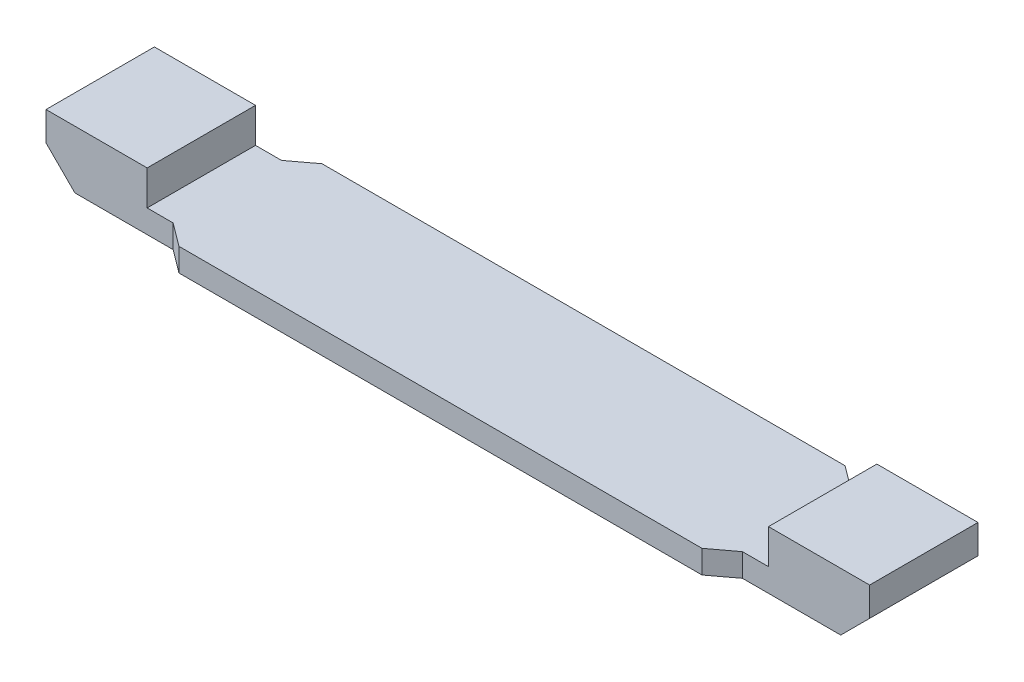
SolidWorks part; units mm, degrees
material "Rubber"
ref_plane "Front Plane" through (0, 0, 0) normal (0, 0, 1) x (1, 0, 0)
ref_plane "Top Plane" through (0, 0, 0) normal (0, 1, 0) x (1, 0, 0)
ref_plane "Right Plane" through (0, 0, 0) normal (1, 0, 0) x (0, 0, -1)
sketch "Sketch1" plane through (0, 0, 0) normal (0, 1, 0) x (1, 0, 0)
  line L1 (0, 0) -> (285, 0)
  line L2 (0, 0) -> (0, 71.5)
  line L3 (0, 71.5) -> (285, 71.5)
  line L4 (285, 0) -> (285, 71.5)
  dimension "D1" = 71.5
  dimension "D2" = 285
extrude "Boss-Extrude1" add sketch "Sketch1" along normal blind 8
sketch "Sketch2" plane through (0, 8, 0) normal (0, 1, 0) x (1, 0, 0)
  line L0 (0, 0) -> (285, 0) construction
  line L1 (0, 71.5) -> (35, 71.5)
  line L2 (0, 71.5) -> (0, 0)
  line L3 (0, 0) -> (35, 0)
  line L4 (35, 71.5) -> (35, 0)
  line L6 (285, 71.5) -> (250, 71.5)
  line L7 (285, 71.5) -> (285, 0)
  line L8 (285, 0) -> (250, 0)
  line L9 (250, 71.5) -> (250, 0)
  dimension "D1" = 35
  dimension "D2" = 35
extrude "Boss-Extrude2" add sketch "Sketch2" along normal blind 12
sketch "Sketch3" plane through (0, 0, 0) normal (-1, 0, 0) x (0, 0, 1)
  line L0 (-71.5, 20) -> (0, 20) construction
  line L1 (-71.5, 20) -> (-71.5, 0) construction
  circle A0 centre (-31.5, 75) radius 60
  dimension "D2" = 120
  dimension "D1" = 55
  dimension "D3" = 40
extrude "Cut-Extrude1" [suppressed] cut sketch "Sketch3" against normal through all
sketch "Sketch4" plane through (0, 0, 0) normal (0, -1, 0) x (1, 0, 0)
  line L0 (0, -17) -> (44, -17)
  line L1 (0, -71.5) -> (0, 0) construction
  line L2 (44, -17) -> (52, -11)
  line L3 (142.5, 0) -> (142.5, -71.5) construction
  line L4 (0, 0) -> (285, 0) construction
  line L5 (285, -71.5) -> (0, -71.5) construction
  line L6 (0, -17) -> (0, 0)
  line L7 (0, 0) -> (285, 0)
  line L8 (52, -11) -> (233, -11)
  line L9 (0, -35.75) -> (285, -35.75) construction
  line L10 (285, 0) -> (285, -71.5) construction
  line L11 (241, -17) -> (233, -11)
  line L12 (285, -17) -> (285, 0)
  line L13 (285, -17) -> (241, -17)
  line L14 (44, -54.5) -> (52, -60.5)
  line L15 (0, -54.5) -> (44, -54.5)
  line L16 (0, -54.5) -> (0, -71.5)
  line L17 (0, -71.5) -> (285, -71.5)
  line L18 (285, -54.5) -> (285, -71.5)
  line L19 (285, -54.5) -> (241, -54.5)
  line L20 (241, -54.5) -> (233, -60.5)
  line L21 (52, -60.5) -> (233, -60.5)
  point P19 (142.5, -11)
  dimension "D1" = 44
  dimension "D2" = 6
  dimension "D3" = 17
  dimension "D4" = 8
extrude "Cut-Extrude2" cut sketch "Sketch4" against normal through all
chamfer "Chamfer1" distance 10 angle 45 2 edges at (0, 0, -35.75) (285, 0, -35.75)
